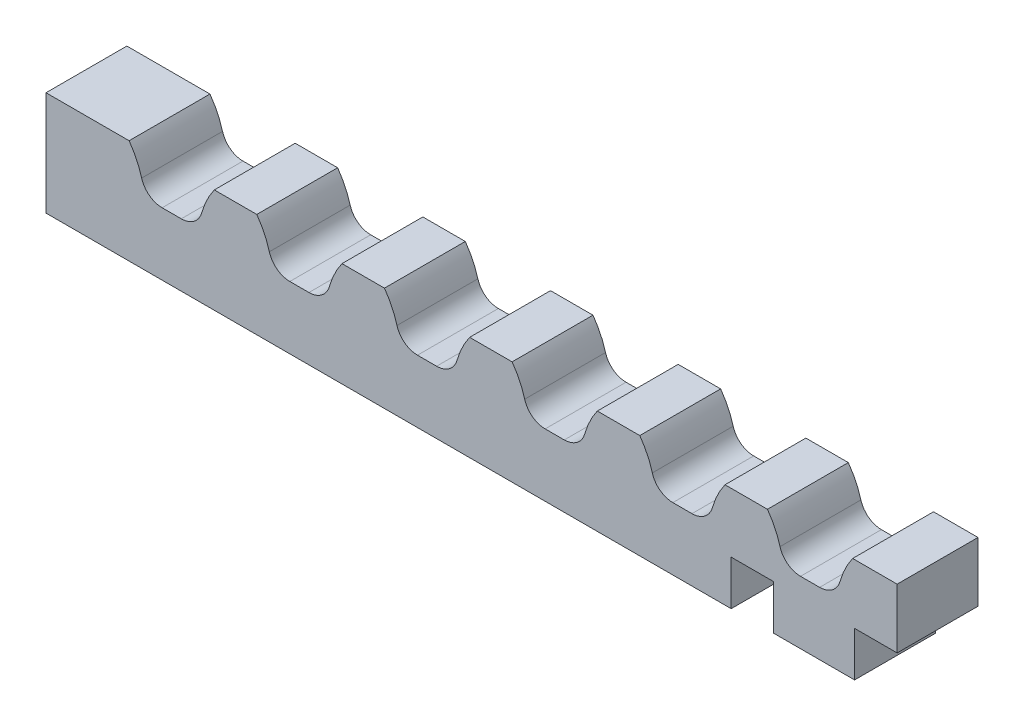
SolidWorks part; units mm, degrees
ref_plane "Alzado" through (0, 0, 0) normal (0, 0, 1) x (1, 0, 0)
ref_plane "Planta" through (0, 0, 0) normal (0, 1, 0) x (1, 0, 0)
ref_plane "Vista lateral" through (0, 0, 0) normal (1, 0, 0) x (0, 0, -1)
sketch "Croquis4" plane through (0, 0, 0) normal (0, 0, 1) x (1, 0, 0)
  line L1 (-20, -2.45) -> (20, -2.45)
  line L2 (-20, -2.45) -> (-20, 2.45)
  line L3 (-20, 2.45) -> (20, 2.45)
  line L4 (20, -2.45) -> (20, 2.45)
  line L5 (-20, -2.45) -> (20, 2.45) construction
  line L6 (-20, 2.45) -> (20, -2.45) construction
  point P0 (0, 0)
  dimension "D1" = 40
  dimension "D2" = 4.9
extrude "Saliente-Extruir1" add sketch "Croquis4" along normal blind 3.8 contours L3 L4 L1 L2
sketch "Croquis5" plane through (0, 0, 3.8) normal (0, 0, 1) x (1, 0, 0)
  line L5 (-20, 0) -> (0, 0) construction
  line L7 (-20, -2.45) -> (-20, 2.45) construction
  line L8 (-12.5923, 2.5) -> (-12.5923, -22.5) construction
  line L10 (-12.5923, -10) -> (-8.317, 1.7462) construction
  line L11 (-12.5923, 1.5) -> (-8.8962, 0.1548) construction
  line L12 (-12.8145, 0.4976) -> (-22.2978, 0.4976) construction
  line L13 (-14.0923, 0.4976) -> (-14.0923, 3.8816) construction
  line L14 (-16.1224, 2.4888) -> (-12.0621, 2.4888)
  line L15 (-15.37, 0.4976) -> (-12.8145, 0.4976)
  circle A2 centre (-12.5923, -10) radius 12.5 construction
  circle A3 centre (-12.5923, -10) radius 11.5 construction
  circle A4 centre (-12.5923, -10) radius 10.5 construction
  arc A5 (-4.9708, -0.0923) -> (-4.9661, 0) centre (-8.8962, 0.1548) ccw
  arc A6 (-12.0621, 2.4888) -> (-12.8145, 0.4976) centre (-8.8962, 0.1548) ccw
  arc A7 (-16.1224, 2.4888) -> (-15.37, 0.4976) centre (-19.2883, 0.1548) cw
  dimension "D1" = 25
  dimension "D2" = 23
  dimension "D3" = 21
  dimension "D4" = 20
  dimension "D5" = 1.5
extrude "Cortar-Extruir1" cut sketch "Croquis5" along direction (0, 0, -1) on the side against the normal blind 5 contours A7 L15 A6 L14
fillet "Redondeo1" radius 1 2 edges at (-15.37, 0.4976, 1.9) (-12.8145, 0.4976, 1.9)
pattern_linear "MatrizL1" count 6 spacing 6 along (1, 0, 0) of "Cortar-Extruir1", "Redondeo1"
sketch "Croquis7" plane through (0, 0, 3.8) normal (0, 0, 1) x (1, 0, 0)
  line L0 (-20, -2.45) -> (20, -2.45) construction
  line L1 (14.2, -4.55) -> (18, -4.55) construction
  line L2 (14.2, -4.55) -> (14.2, -0.35) construction
  line L3 (14.2, -0.35) -> (18, -0.35) construction
  line L4 (18, -4.55) -> (18, -0.35) construction
  line L5 (14.2, -4.55) -> (18, -0.35) construction
  line L6 (14.2, -0.35) -> (18, -4.55) construction
  line L7 (20, -2.45) -> (20, 2.45) construction
  line L8 (20, -2.45) -> (18, -2.45) construction
  line L9 (14.2, -2.45) -> (13.2, -2.45) construction
  line L10 (20, -4.55) -> (18, -4.55)
  line L11 (20, -4.55) -> (20, -0.35)
  line L12 (20, -0.35) -> (18, -0.35)
  line L13 (18, -4.55) -> (18, -0.35)
  line L14 (20, -4.55) -> (18, -0.35) construction
  line L15 (20, -0.35) -> (18, -4.55) construction
  line L17 (12.2, -4.55) -> (14.2, -4.55)
  line L18 (12.2, -4.55) -> (12.2, -0.35)
  line L19 (12.2, -0.35) -> (14.2, -0.35)
  line L20 (14.2, -4.55) -> (14.2, -0.35)
  line L21 (12.2, -4.55) -> (14.2, -0.35) construction
  line L22 (12.2, -0.35) -> (14.2, -4.55) construction
  point P0 (16.1, -2.45)
  point P12 (19, -2.45)
  dimension "D1" = 2
  dimension "D2" = 3.8
  dimension "D3" = 4.2
  dimension "D4" = 1
extrude "Cortar-Extruir2" cut sketch "Croquis7" against normal blind 10
